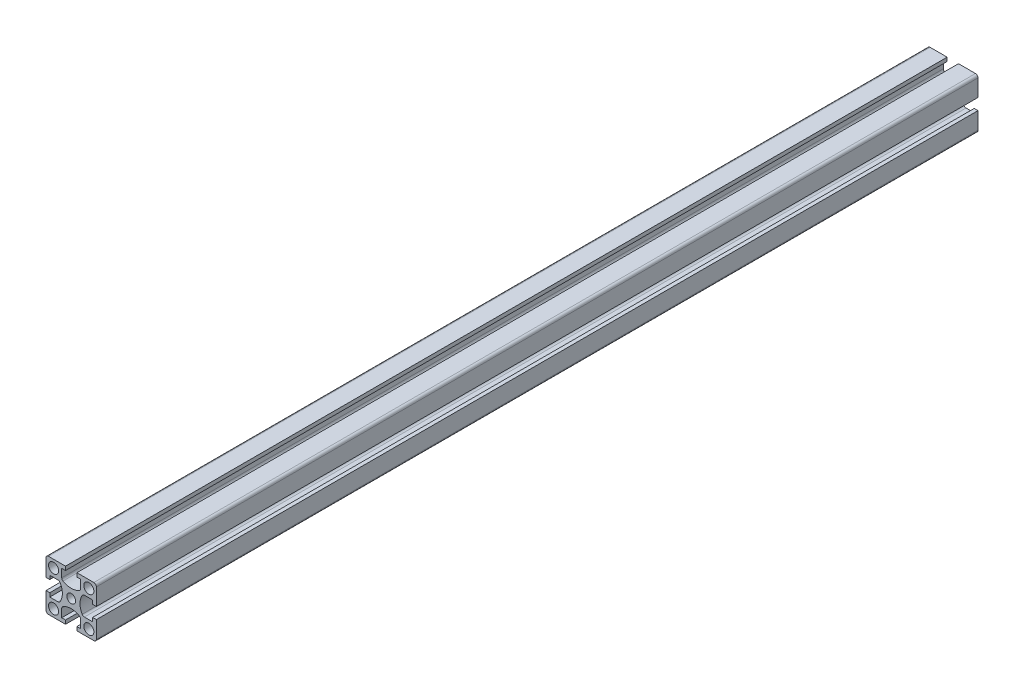
SolidWorks part; units mm, degrees
ref_plane "Front Plane" through (0, 0, 0) normal (0, 0, 1) x (1, 0, 0)
ref_plane "Top Plane" through (0, 0, 0) normal (0, 1, 0) x (1, 0, 0)
ref_plane "Right Plane" through (0, 0, 0) normal (1, 0, 0) x (0, 0, -1)
sketch "Sketch1" plane through (0, 0, 0) normal (0, 0, 1) x (1, 0, 0)
  line L64 (-10, 9) -> (-10, 2.25)
  line L65 (-10, 2.25) -> (-8.5, 2.25)
  line L66 (-8.5, 2.25) -> (-8.5, 3.75)
  line L67 (-8.5, 3.75) -> (-5.2369, 3.75)
  line L68 (-5.2369, -3.75) -> (-8.5, -3.75)
  line L69 (-8.5, -3.75) -> (-8.5, -2.25)
  line L70 (-8.5, -2.25) -> (-10, -2.25)
  line L71 (-10, -2.25) -> (-10, -9)
  line L72 (-9, -10) -> (-2.25, -10)
  line L73 (-2.25, -10) -> (-2.25, -8.5)
  line L74 (-2.25, -8.5) -> (-3.75, -8.5)
  line L75 (-3.75, -8.5) -> (-3.75, -5.2369)
  line L76 (3.75, -5.2369) -> (3.75, -8.5)
  line L77 (3.75, -8.5) -> (2.25, -8.5)
  line L78 (2.25, -8.5) -> (2.25, -10)
  line L79 (2.25, -10) -> (9, -10)
  line L80 (10, -9) -> (10, -2.25)
  line L81 (10, -2.25) -> (8.5, -2.25)
  line L82 (8.5, -2.25) -> (8.5, -3.75)
  line L83 (8.5, -3.75) -> (5.2369, -3.75)
  line L84 (5.2369, 3.75) -> (8.5, 3.75)
  line L85 (8.5, 3.75) -> (8.5, 2.25)
  line L86 (8.5, 2.25) -> (10, 2.25)
  line L87 (10, 2.25) -> (10, 9)
  line L88 (9, 10) -> (2.25, 10)
  line L89 (2.25, 10) -> (2.25, 8.5)
  line L90 (2.25, 8.5) -> (3.75, 8.5)
  line L91 (3.75, 8.5) -> (3.75, 5.2369)
  line L92 (-3.75, 5.2369) -> (-3.75, 8.5)
  line L93 (-3.75, 8.5) -> (-2.25, 8.5)
  line L94 (-2.25, 8.5) -> (-2.25, 10)
  line L95 (-2.25, 10) -> (-9, 10)
  circle A5 centre (-7, -7) radius 2
  circle A6 centre (7, -7) radius 2
  circle A7 centre (7, 7) radius 2
  circle A8 centre (0, 0) radius 1.75
  circle A9 centre (-7, 7) radius 2
  arc A32 (-9, 10) -> (-10, 9) centre (-9, 9) ccw
  arc A33 (-4.3708, 3.25) -> (-5.2369, 3.75) centre (-5.2369, 2.75) ccw
  arc A34 (-4.3708, -3.25) -> (-4.3708, 3.25) centre (-10, 0) ccw
  arc A35 (-5.2369, -3.75) -> (-4.3708, -3.25) centre (-5.2369, -2.75) ccw
  arc A36 (-10, -9) -> (-9, -10) centre (-9, -9) ccw
  arc A37 (-3.25, -4.3708) -> (-3.75, -5.2369) centre (-2.75, -5.2369) ccw
  arc A38 (3.25, -4.3708) -> (-3.25, -4.3708) centre (0, -10) ccw
  arc A39 (3.75, -5.2369) -> (3.25, -4.3708) centre (2.75, -5.2369) ccw
  arc A40 (9, -10) -> (10, -9) centre (9, -9) ccw
  arc A41 (4.3708, -3.25) -> (5.2369, -3.75) centre (5.2369, -2.75) ccw
  arc A42 (4.3708, 3.25) -> (4.3708, -3.25) centre (10, 0) ccw
  arc A43 (5.2369, 3.75) -> (4.3708, 3.25) centre (5.2369, 2.75) ccw
  arc A44 (10, 9) -> (9, 10) centre (9, 9) ccw
  arc A45 (3.25, 4.3708) -> (3.75, 5.2369) centre (2.75, 5.2369) ccw
  arc A46 (-3.25, 4.3708) -> (3.25, 4.3708) centre (0, 10) ccw
  arc A47 (-3.75, 5.2369) -> (-3.25, 4.3708) centre (-2.75, 5.2369) ccw
extrude "Boss-Extrude1" add sketch "Sketch1" along normal blind 350
